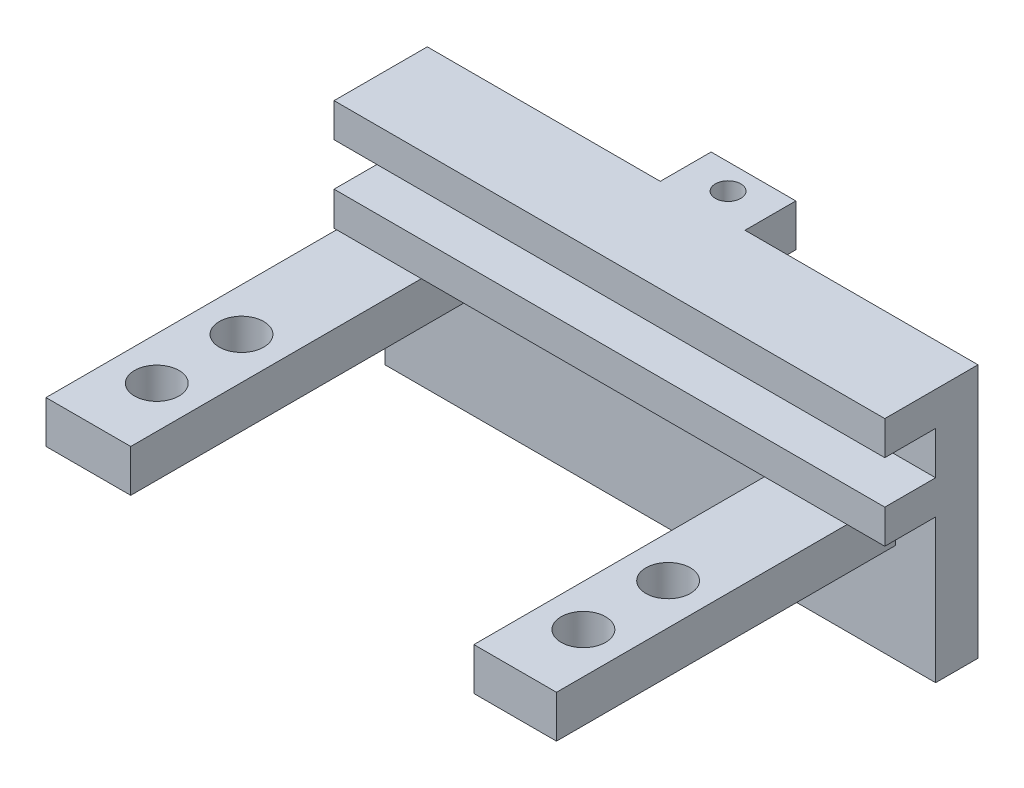
SolidWorks part; units mm, degrees
ref_plane "Plan de face" through (0, 0, 0) normal (0, 0, 1) x (1, 0, 0)
ref_plane "Plan de dessus" through (0, 0, 0) normal (0, 1, 0) x (1, 0, 0)
ref_plane "Plan de droite" through (0, 0, 0) normal (1, 0, 0) x (0, 0, -1)
sketch "Esquisse1" plane through (0, 0, 0) normal (0, 0, 1) x (1, 0, 0)
  line L1 (-30, 15) -> (30, 15)
  line L2 (-30, 15) -> (-30, -15)
  line L3 (-30, -15) -> (30, -15)
  line L4 (30, 15) -> (30, -15)
  line L5 (-30, 15) -> (30, -15) construction
  line L6 (-30, -15) -> (30, 15) construction
  point P0 (0, 0)
  dimension "D1" = 30
  dimension "D2" = 60
extrude "Boss.-Extru.1" add sketch "Esquisse1" along normal blind 5
sketch "Esquisse2" plane through (0, 0, 5) normal (0, 0, 1) x (1, 0, 0)
  line L0 (-30, 11) -> (30, 11)
  line L2 (-30, 5.95) -> (30, 5.95)
  line L3 (-30, 5.95) -> (-30, 1.95)
  line L4 (30, -15) -> (30, 15)
  line L5 (30, 15) -> (-30, 15)
  line L6 (-30, 15) -> (-30, -15)
  line L7 (-30, -15) -> (30, -15)
  line L8 (30, -15) -> (30, 15)
  line L9 (30, 15) -> (-30, 15)
  line L10 (-30, 15) -> (-30, -15)
  line L11 (-30, -15) -> (30, -15)
  line L12 (-30, 1.95) -> (30, 1.95)
  line L13 (30, 5.95) -> (30, 1.95)
  line M6 (30, -15) -> (30, 15)
  line M7 (30, 15) -> (-30, 15)
  line M8 (-30, 15) -> (-30, -15)
  dimension "D2" = 4
  dimension "D3" = 4
  dimension "D4" = 5.05
  dimension "D1" = 0
extrude "Boss.-Extru.2" add sketch "Esquisse2" along normal blind 6 contours L0 M8 M6 M7 | L3 L2 L13 L12
sketch "Esquisse3" plane through (0, 0, 5) normal (0, 0, 1) x (1, 0, 0)
  line L0 (-30, 1.95) -> (-30, -15) construction
  line L1 (-30, -3.35) -> (-25, -3.35)
  line L2 (-30, -3.35) -> (-30, 1.65)
  line L3 (-30, 1.65) -> (-25, 1.65)
  line L4 (-25, -3.35) -> (-25, 1.65)
  line L5 (-30.75, -3.35) -> (-31.75, -3.35) construction
  line L7 (22.25, -3.35) -> (17.25, -3.35)
  line L8 (22.25, -3.35) -> (22.25, 1.65)
  line L9 (22.25, 1.65) -> (17.25, 1.65)
  line L10 (17.25, -3.35) -> (17.25, 1.65)
  dimension "D1" = 5
  dimension "D2" = 5
  dimension "D3" = 5
  dimension "D4" = 5
extrude "Boss.-Extru.3" add sketch "Esquisse3" along normal blind 40
sketch "Esquisse4" plane through (0, -3.35, 0) normal (0, -1, 0) x (1, 0, 0)
  circle A0 centre (-29.925, 37) radius 2.625
  circle A1 centre (-29.925, 27) radius 2.625
  circle A2 centre (20.425, 37) radius 2.625
  circle A3 centre (20.425, 27) radius 2.625
sketch "Esquisse5" plane through (-30, 0, 0) normal (-1, 0, 0) x (0, 0, 1)
  line L0 (5, 1.65) -> (5, -3.35)
  line L14 (0, 15) -> (0, -15)
  line L15 (0, -15) -> (5, -15)
  line L16 (5, -15) -> (5, -3.35)
  line L17 (5, -3.35) -> (45, -3.35)
  line L18 (45, -3.35) -> (45, 1.65)
  line L19 (45, 1.65) -> (5, 1.65)
  line L20 (5, 1.65) -> (5, 1.95)
  line L21 (5, 1.95) -> (11, 1.95)
  line L22 (11, 1.95) -> (11, 5.95)
  line L23 (11, 5.95) -> (5, 5.95)
  line L24 (5, 5.95) -> (5, 11)
  line L25 (5, 11) -> (11, 11)
  line L26 (11, 11) -> (11, 15)
  line L27 (11, 15) -> (0, 15)
  line L28 (0, 15) -> (0, -15)
  line L29 (0, -15) -> (5, -15)
  line L30 (5, -15) -> (5, -3.35)
  line L31 (5, -3.35) -> (45, -3.35)
  line L32 (45, -3.35) -> (45, 1.65)
  line L33 (45, 1.65) -> (5, 1.65)
  line L34 (5, 1.65) -> (5, 1.95)
  line L35 (5, 1.95) -> (11, 1.95)
  line L36 (11, 1.95) -> (11, 5.95)
  line L37 (11, 5.95) -> (5, 5.95)
  line L38 (5, 5.95) -> (5, 11)
  line L39 (5, 11) -> (11, 11)
  line L40 (11, 11) -> (11, 15)
  line L41 (11, 15) -> (0, 15)
  line M18 (5, -3.35) -> (45, -3.35)
  line M19 (45, -3.35) -> (45, 1.65)
  line M20 (45, 1.65) -> (5, 1.65)
  dimension "D1" = 0
extrude "Boss.-Extru.4" add sketch "Esquisse5" along normal blind 3 contours L0 M20 M18 M19
sketch "Esquisse6" plane through (22.25, 0, 0) normal (1, 0, 0) x (0, 0, -1)
  line L4 (-5, -3.35) -> (-5, 1.65)
  line L5 (-5, 1.65) -> (-45, 1.65)
  line L6 (-45, 1.65) -> (-45, -3.35)
  line L7 (-45, -3.35) -> (-5, -3.35)
  line L8 (-5, -3.35) -> (-5, 1.65)
  line L9 (-5, 1.65) -> (-45, 1.65)
  line L10 (-45, 1.65) -> (-45, -3.35)
  line L11 (-45, -3.35) -> (-5, -3.35)
  dimension "D1" = 0
extrude "Boss.-Extru.5" add sketch "Esquisse6" along normal blind 3
sketch "Esquisse7" plane through (0, -3.35, 0) normal (0, -1, 0) x (1, 0, 0)
  circle A0 centre (20.425, 37) radius 2.625 construction
  circle A1 centre (20.425, 27) radius 2.625 construction
  circle A2 centre (-29.925, 27) radius 2.625 construction
  circle A3 centre (-29.925, 37) radius 2.625 construction
  circle A4 centre (20.425, 37) radius 2.625
  circle A5 centre (20.425, 27) radius 2.625
  circle A6 centre (-29.925, 27) radius 2.625
  circle A7 centre (-29.925, 37) radius 2.625
extrude "Enlèv. mat.-Extru.1" cut sketch "Esquisse7" against normal through all
sketch "Esquisse8" plane through (-25, 0, 0) normal (1, 0, 0) x (0, 0, -1)
  line L4 (-5, -3.35) -> (-5, 1.65)
  line L5 (-5, 1.65) -> (-45, 1.65)
  line L6 (-45, 1.65) -> (-45, -3.35)
  line L7 (-45, -3.35) -> (-5, -3.35)
  line L8 (-5, -3.35) -> (-5, 1.65)
  line L9 (-5, 1.65) -> (-45, 1.65)
  line L10 (-45, 1.65) -> (-45, -3.35)
  line L11 (-45, -3.35) -> (-5, -3.35)
  dimension "D1" = 0
sketch "Esquisse9" plane through (-30, 0, 0) normal (-1, 0, 0) x (0, 0, 1)
  line L12 (5, -3.35) -> (5, 1.65)
  line L13 (5, 1.65) -> (5, 1.95)
  line L14 (5, 1.95) -> (11, 1.95)
  line L15 (11, 1.95) -> (11, 5.95)
  line L16 (11, 5.95) -> (5, 5.95)
  line L17 (5, 5.95) -> (5, 11)
  line L18 (5, 11) -> (11, 11)
  line L19 (11, 11) -> (11, 15)
  line L20 (11, 15) -> (0, 15)
  line L21 (0, 15) -> (0, -15)
  line L22 (0, -15) -> (5, -15)
  line L23 (5, -15) -> (5, -3.35)
  line L24 (5, -3.35) -> (5, 1.65)
  line L25 (5, 1.65) -> (5, 1.95)
  line L26 (5, 1.95) -> (11, 1.95)
  line L27 (11, 1.95) -> (11, 5.95)
  line L28 (11, 5.95) -> (5, 5.95)
  line L29 (5, 5.95) -> (5, 11)
  line L30 (5, 11) -> (11, 11)
  line L31 (11, 11) -> (11, 15)
  line L32 (11, 15) -> (0, 15)
  line L33 (0, 15) -> (0, -15)
  line L34 (0, -15) -> (5, -15)
  line L35 (5, -15) -> (5, -3.35)
  dimension "D1" = 0
extrude "Boss.-Extru.6" add sketch "Esquisse9" along normal blind 5
sketch "Esquisse10" plane through (-33, 0, 0) normal (-1, 0, 0) x (0, 0, 1)
  line L4 (45, 1.65) -> (5, 1.65)
  line L5 (5, 1.65) -> (5, -3.35)
  line L6 (5, -3.35) -> (45, -3.35)
  line L7 (45, -3.35) -> (45, 1.65)
  line L8 (45, 1.65) -> (5, 1.65)
  line L9 (5, 1.65) -> (5, -3.35)
  line L10 (5, -3.35) -> (45, -3.35)
  line L11 (45, -3.35) -> (45, 1.65)
  dimension "D1" = 0
extrude "Boss.-Extru.7" add sketch "Esquisse10" along normal through all
sketch "Esquisse11" plane through (17.25, 0, 0) normal (-1, 0, 0) x (0, 0, 1)
  line L4 (5, 1.65) -> (5, -3.35)
  line L5 (5, -3.35) -> (45, -3.35)
  line L6 (45, -3.35) -> (45, 1.65)
  line L7 (45, 1.65) -> (5, 1.65)
  line L8 (5, 1.65) -> (5, -3.35)
  line L9 (5, -3.35) -> (45, -3.35)
  line L10 (45, -3.35) -> (45, 1.65)
  line L11 (45, 1.65) -> (5, 1.65)
  dimension "D1" = 0
extrude "Boss.-Extru.8" add sketch "Esquisse11" along normal blind 1.75
sketch "Esquisse12" plane through (0, -15, 0) normal (0, -1, 0) x (1, 0, 0)
  line L0 (-2.5, -8.9829) -> (-2.5, 27.7475) construction
  line L1 (-35, 0) -> (30, 0) construction
  line L2 (-7.5, -6) -> (2.5, -6)
  line L3 (-7.5, -6) -> (-7.5, 0)
  line L4 (-7.5, 0) -> (2.5, 0)
  line L5 (2.5, -6) -> (2.5, 0)
  line L6 (-7.5, -6) -> (2.5, 0) construction
  line L7 (-7.5, 0) -> (2.5, -6) construction
  line L8 (-35, 5) -> (-35, 45) construction
  circle A0 centre (-2.5, -3) radius 1.5
  point P2 (-2.5, -3)
  dimension "D4" = 3
  dimension "D1" = 10
  dimension "D2" = 6
  dimension "D3" = 32.5
sketch "Esquisse13" plane through (0, 15, 0) normal (0, 1, 0) x (1, 0, 0)
  line L4 (2.5, 6) -> (-7.5, 6)
  line L5 (2.5, 0) -> (2.5, 6)
  line L6 (-7.5, 0) -> (2.5, 0)
  line L7 (-7.5, 6) -> (-7.5, 0)
  line L8 (2.5, 6) -> (-7.5, 6)
  line L9 (2.5, 0) -> (2.5, 6)
  line L10 (-7.5, 0) -> (2.5, 0)
  line L11 (-7.5, 6) -> (-7.5, 0)
  circle A1 centre (-2.5, 3) radius 1.5
  circle A2 centre (-2.5, 3) radius 1.5
  dimension "D1" = 0
  dimension "D2" = 0
extrude "Boss.-Extru.10" add sketch "Esquisse13" against normal blind 5
